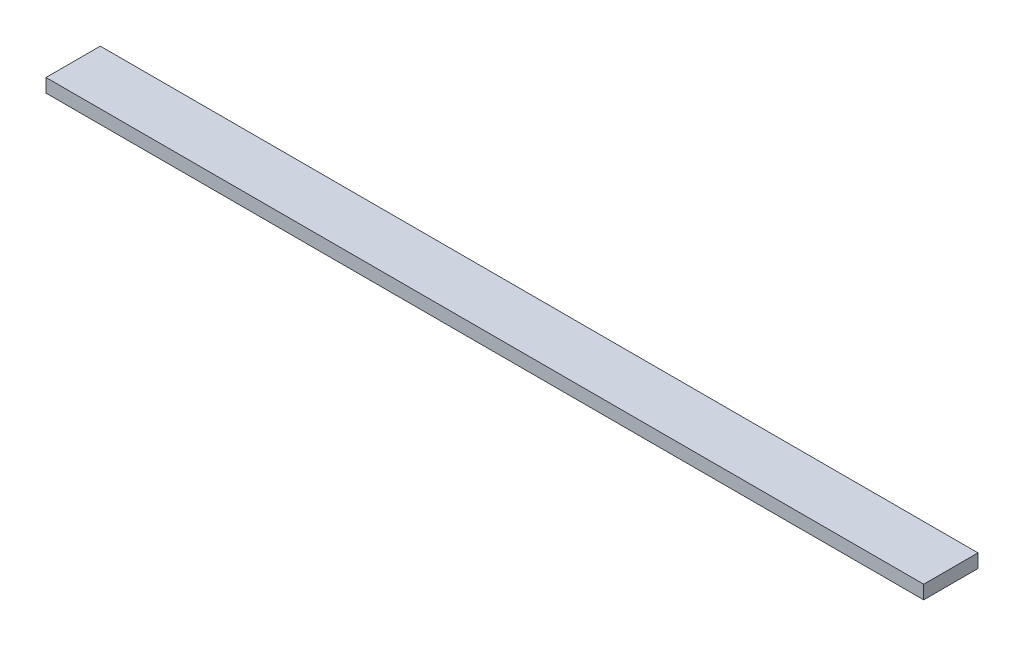
SolidWorks part; units mm, degrees
ref_plane "Front Plane" through (0, 0, 0) normal (0, 0, 1) x (1, 0, 0)
ref_plane "Top Plane" through (0, 0, 0) normal (0, 1, 0) x (1, 0, 0)
ref_plane "Right Plane" through (0, 0, 0) normal (1, 0, 0) x (0, 0, -1)
sketch "Sketch1" plane through (0, 0, 0) normal (0, 1, 0) x (1, 0, 0)
  line L1 (0, 0) -> (194, 0)
  line L2 (0, 0) -> (0, 12)
  line L3 (0, 12) -> (194, 12)
  line L4 (194, 0) -> (194, 12)
  dimension "D1" = 12
  dimension "D2" = 194
extrude "Boss-Extrude1" add sketch "Sketch1" along normal blind 3
